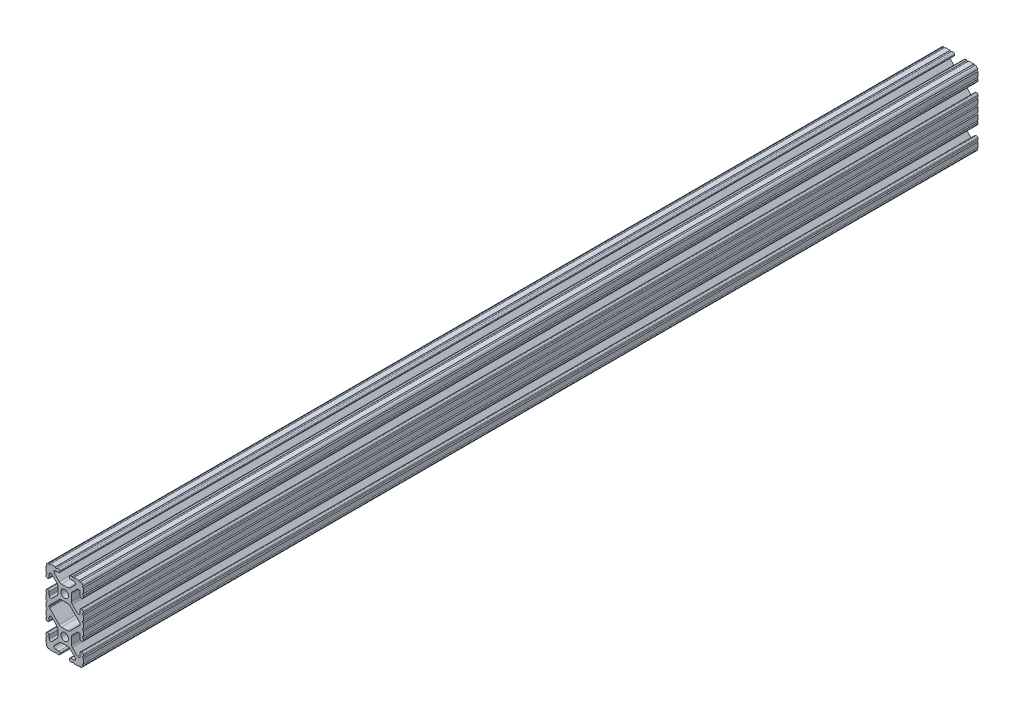
SolidWorks part; units mm, degrees
ref_plane "Front Plane" through (0, 0, 0) normal (0, 0, 1) x (1, 0, 0)
ref_plane "Top Plane" through (0, 0, 0) normal (0, 1, 0) x (1, 0, 0)
ref_plane "Right Plane" through (0, 0, 0) normal (1, 0, 0) x (0, 0, -1)
sketch "Sketch2" plane through (0, 0, 0) normal (0, 0, 1) x (1, 0, 0)
  line L0 (0, 25.4) -> (0, -25.4) construction
  line L1 (-12.7, 0) -> (12.7, 0) construction
  line L2 (3.2512, -25.4) -> (12.7, -25.4)
  line L3 (12.7, -25.4) -> (12.7, -15.9512)
  line L4 (3.2512, -25.4) -> (3.2512, -23.1902)
  line L5 (3.2512, -23.1902) -> (8.9276, -23.1902)
  line L6 (8.9276, -23.1902) -> (3.0856, -17.3482)
  line L7 (0, -12.7) -> (12.7, -25.4) construction
  line L8 (12.7, -15.9512) -> (10.4902, -15.9512)
  line L9 (10.4902, -15.9512) -> (10.4902, -21.6276)
  line L10 (10.4902, -21.6276) -> (4.6482, -15.7856)
  circle A0 centre (0, -12.7) radius 2.6035
  arc A1 (6.3485, -23.1902) -> (7.1039, -21.3665) centre (6.3485, -22.1219) ccw construction
  point P8 (0, -17.3482)
  dimension "Center Hole Diameter" = 5.207
  dimension "Rail Height" = 50.8
  dimension "Rail Width" = 25.4
  dimension "T-Slot Width" = 6.5024
  dimension "Slot Inner Width" = 14.8336
  dimension "Thickness" = 2.2098
  dimension "Slot Depth" = 5.842
  dimension "D1" = 2.2098
  dimension "C to C" = 25.4
sketch "Sketch3" plane through (0, 0, 0) normal (1, 0, 0) x (0, 0, -1)
  line L0 (-304.8, -25.4) -> (304.8, -25.4) construction
  line L1 (-279.4, 0) -> (279.4, 0) construction
  dimension "Length" = 609.6
  dimension "D1" = 25.4
sketch "Sketch4" plane through (0, 0, 0) normal (0, 0, 1) x (1, 0, 0)
  line L0 (4.1904, -25.4) -> (10.1173, -25.4)
  line L1 (3.2512, -25.4) -> (12.7, -25.4) construction
  line L2 (3.2512, -25.4) -> (3.2512, -23.1902) construction
  line L3 (3.2512, -23.1902) -> (8.9276, -23.1902) construction
  line L4 (3.2512, -24.1294) -> (3.2512, -24.4608)
  line L5 (4.1904, -23.1902) -> (6.3485, -23.1902)
  line L6 (0, -17.3482) -> (2.164, -17.3482)
  line L7 (8.9276, -23.1902) -> (3.0856, -17.3482) construction
  line L8 (3.7373, -17.9999) -> (7.1039, -21.3665)
  line L9 (12.7, -25.4) -> (12.7, -15.9512) construction
  line L10 (10.4902, -21.6276) -> (4.6482, -15.7856) construction
  line L11 (10.4902, -15.9512) -> (10.4902, -21.6276) construction
  line L12 (10.4902, -19.0485) -> (10.4902, -16.8904)
  line L13 (12.7, -15.9512) -> (10.4902, -15.9512) construction
  line L14 (11.4294, -15.9512) -> (11.7608, -15.9512)
  line L15 (12.7, -16.8904) -> (12.7, -22.8173)
  line L16 (8.6665, -19.8039) -> (5.2999, -16.4373)
  line L17 (4.6482, -12.7) -> (4.6482, -14.864)
  line L19 (0, -17.3482) -> (0, -15.3035)
  line L20 (0, 25.4) -> (0, -25.4) construction
  line L21 (4.6482, -12.7) -> (2.6035, -12.7)
  arc A0 (3.2512, -24.4608) -> (4.1904, -25.4) centre (4.1904, -24.4608) ccw
  circle A1 centre (0, -12.7) radius 2.6035 construction
  arc A2 (3.2512, -24.1294) -> (4.1904, -23.1902) centre (4.1904, -24.1294) cw
  arc A3 (6.3485, -23.1902) -> (7.1039, -21.3665) centre (6.3485, -22.1219) ccw
  arc A4 (2.164, -17.3482) -> (3.7373, -17.9999) centre (2.164, -19.5732) cw
  arc A5 (10.1173, -25.4) -> (12.7, -22.8173) centre (10.1173, -22.8173) ccw
  arc A6 (8.6665, -19.8039) -> (10.4902, -19.0485) centre (9.4219, -19.0485) ccw
  arc A7 (10.4902, -16.8904) -> (11.4294, -15.9512) centre (11.4294, -16.8904) cw
  arc A8 (11.7608, -15.9512) -> (12.7, -16.8904) centre (11.7608, -16.8904) cw
  arc A9 (5.2999, -16.4373) -> (4.6482, -14.864) centre (6.8732, -14.864) cw
  arc A11 (0, -15.3035) -> (2.6035, -12.7) centre (0, -12.7) ccw
  dimension "D1" = 2.5827
  dimension "D2" = 2.225
  dimension "D3" = 0.9392
extrude "Boss-Extrude1" add sketch "Sketch4" along normal mid plane 609.6
sketch "Sketch5" plane through (0, 0, 0) normal (0, 0, 1) x (1, 0, 0)
  line L0 (3.2512, -25.4) -> (12.7, -25.4) construction
  line L1 (4.1904, -23.1902) -> (6.3485, -23.1902) construction
  line L3 (0, -12.7) -> (12.7, -25.4) construction
  line L4 (6.3485, -23.1902) -> (6.3485, -25.4) construction
  line L5 (8.9276, -23.1902) -> (3.0856, -17.3482) construction
  circle A0 centre (10.3562, -25.4) radius 0.5524
  circle A1 centre (5.796, -25.4) radius 0.5524
  circle A2 centre (12.7, -23.0562) radius 0.5524
  circle A3 centre (12.7, -18.496) radius 0.5524
  point P10 (5.2694, -23.1902)
  point P12 (9.4219, -19.0485)
  dimension "D1" = 1.1049
extrude "Cut-Extrude1" cut sketch "Sketch5" against normal through all both and the other way through all
mirror "Mirror1" about plane through (4.6482, -12.7, 304.8) normal (0, -1, 0) of bodies 137 134
sketch "Sketch6" plane through (0, 0, 0) normal (0, 0, 1) x (1, 0, 0)
  line L0 (12.7, -1.7914) -> (12.7, 0)
  line L1 (12.7, 0) -> (9.8037, 0)
  line L2 (-12.7, 0) -> (12.7, 0) construction
  line L3 (9.8037, 0) -> (9.8037, -2.3438)
  line L4 (9.8037, -2.3438) -> (12.1476, -2.3438)
  circle A0 centre (12.7, -2.3438) radius 0.5524 construction
  arc A1 (12.7, -1.7914) -> (12.1476, -2.3438) centre (12.7, -2.3438) ccw
  arc A4 (12.58, -1.8046) -> (12.7, -2.8963) centre (12.7, -2.3438) ccw construction
  arc A6 (9.8037, 0) -> (10.8954, -0.12) centre (10.3562, 0) ccw construction
extrude "Boss-Extrude2" add sketch "Sketch6" along normal mid plane 609.6
sketch "Sketch7" plane through (0, 0, 0) normal (0, 0, 1) x (1, 0, 0)
  line L0 (5.4206, -5.7168) -> (10.3284, -0.809)
  line L1 (3.7373, -7.4001) -> (7.1039, -4.0335) construction
  line L2 (10.4902, -0.4184) -> (10.4902, 0)
  line L3 (0, 0) -> (10.4902, 0)
  line L4 (-12.7, 0) -> (12.7, 0) construction
  line L5 (0, 0) -> (5.4206, -5.7168)
  arc A0 (10.3284, -0.809) -> (10.4902, -0.4184) centre (9.9377, -0.4184) ccw
  arc A3 (12.7, -1.7914) -> (12.7, -2.8963) centre (12.7, -2.3438) ccw construction
extrude "Cut-Extrude2" cut sketch "Sketch7" against normal through all both and the other way through all
mirror "Mirror2" about plane through (0, 0, 0) normal (0, 1, 0) of bodies 139 135
mirror "Mirror3" about plane through (0, 0, 0) normal (1, 0, 0) of bodies 136
equation "\"D1@Boss-Extrude1\"=\"Length@Sketch3\""
equation "\"D1@Sketch2\"=\"Thickness@Sketch2\""
equation "\"D2@Sketch4\"=\"Slot Inner Width@Sketch2\"*0.15"
equation "\"D1@Sketch4\"=\"D3@Sketch4\"*2.75"
equation "\"D3@Sketch4\"=\"Thickness@Sketch2\"*0.425"
equation "\"D1@Sketch5\"=\"Thickness@Sketch2\"*0.5"
equation "\"D1@Boss-Extrude2\"=\"Length@Sketch3\""
